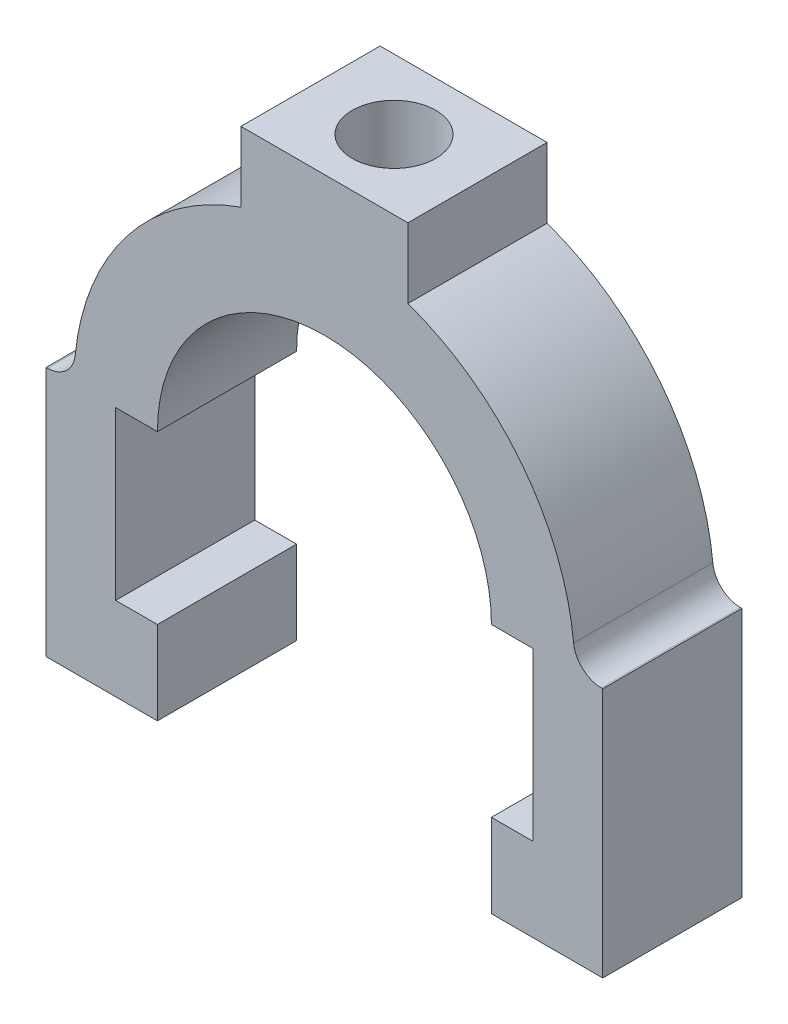
SolidWorks part; units mm, degrees
material "1060 Alloy"
ref_plane "Front Plane" through (0, 0, 0) normal (0, 0, 1) x (1, 0, 0)
ref_plane "Top Plane" through (0, 0, 0) normal (0, 1, 0) x (1, 0, 0)
ref_plane "Right Plane" through (0, 0, 0) normal (1, 0, 0) x (0, 0, -1)
sketch "Sketch2" plane through (0, 0, 0) normal (0, 0, 1) x (1, 0, 0)
  line L0 (-36, 0) -> (-40, 0)
  line L1 (-40, 0) -> (-40, -36)
  line L2 (-40, -36) -> (-24, -36)
  line L3 (-24, -36) -> (-24, -24)
  line L4 (-24, -24) -> (-30, -24)
  line L5 (-14.3487, -11.9996) -> (-13.9678, -12.3805)
  line L6 (-30, -24) -> (-30, 0)
  line L7 (0, 0) -> (0, 36) construction
  line L8 (12, 44) -> (-12, 44)
  line L9 (-12, 44) -> (-12, 33.9411)
  line L10 (12, 44) -> (12, 33.9411)
  line L11 (30, -24) -> (30, 0)
  line L12 (0, 0) -> (0, -35.3639) construction
  line L13 (14.3487, -11.9996) -> (13.9678, -12.3805)
  line L14 (24, -24) -> (30, -24)
  line L15 (24, -36) -> (24, -24)
  line L16 (40, -36) -> (24, -36)
  line L17 (40, 0) -> (40, -36)
  line L18 (36, 0) -> (40, 0)
  line L19 (-30, 0) -> (-24, 0)
  line L20 (24, 0) -> (30, 0)
  arc A0 (-36, 0) -> (-12, 33.9411) centre (0, 0) cw
  arc A2 (12, 33.9411) -> (36, 0) centre (0, 0) cw
  arc A3 (-24, 0) -> (24, 0) centre (0, 0) cw
  dimension "D1" = 10
  dimension "D3" = 16
  dimension "D4" = 36
  dimension "D5" = 24
  dimension "D6" = 6
  dimension "D2" = 40
extrude "Boss-Extrude1" add sketch "Sketch2" against normal blind 20
fillet "Fillet1" radius 4 2 edges at (-36, 0, -10) (36, 0, -10)
sketch "Sketch3" plane through (0, 44, 0) normal (0, 1, 0) x (1, 0, 0)
  circle A0 centre (0, 10) radius 6
  point P0 (0, 10)
  dimension "D1" = 12
extrude "Cut-Extrude2" cut sketch "Sketch3" against normal through all
